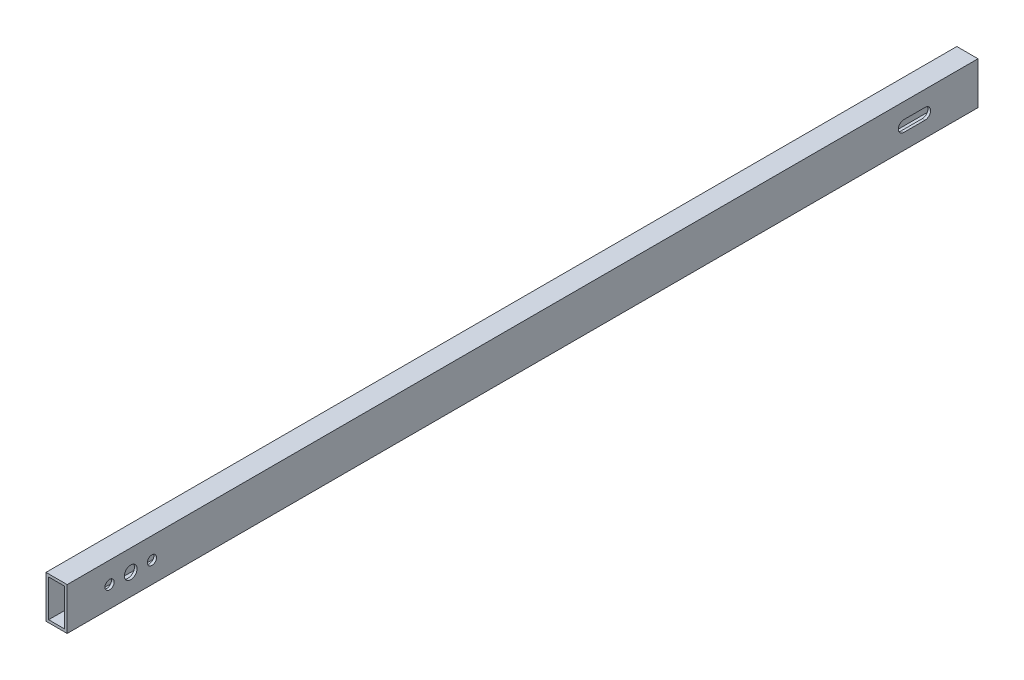
SolidWorks part; units mm, degrees
ref_plane "Front Plane" through (0, 0, 0) normal (0, 0, 1) x (1, 0, 0)
ref_plane "Top Plane" through (0, 0, 0) normal (0, 1, 0) x (1, 0, 0)
ref_plane "Right Plane" through (0, 0, 0) normal (1, 0, 0) x (0, 0, -1)
sketch "Sketch1" plane through (0, 0, 0) normal (0, 0, 1) x (1, 0, 0)
  line L1 (-6.35, -12.7) -> (6.35, -12.7)
  line L2 (-6.35, -12.7) -> (-6.35, 12.7)
  line L3 (-6.35, 12.7) -> (6.35, 12.7)
  line L4 (6.35, -12.7) -> (6.35, 12.7)
  line L6 (-6.35, 12.7) -> (6.35, -12.7) construction
  line L7 (-4.7625, -11.1125) -> (4.7625, -11.1125)
  line L8 (-4.7625, -11.1125) -> (-4.7625, 11.1125)
  line L9 (-4.7625, 11.1125) -> (4.7625, 11.1125)
  line L10 (4.7625, -11.1125) -> (4.7625, 11.1125)
  line L11 (-4.7625, -11.1125) -> (4.7625, 11.1125) construction
  line L12 (-4.7625, 11.1125) -> (4.7625, -11.1125) construction
  point P0 (0, 0)
  point P6 (0, 0)
  dimension "D1" = 25.4
  dimension "D2" = 1.5875
  dimension "D3" = 12.7
  dimension "D4" = 1.5875
  dimension "D5" = 1.5875
extrude "Boss-Extrude1" add sketch "Sketch1" along normal blind 546.1
sketch "Sketch2" plane through (6.35, 0, 0) normal (1, 0, 0) x (0, 0, -1)
  line L0 (-546.1, 0) -> (0, 0) construction
  line L1 (-546.1, -12.7) -> (-546.1, 12.7) construction
  line L2 (-508, 12.7) -> (-508, -12.7) construction
  line L3 (-31.75, 0) -> (-44.45, 0) construction
  line L4 (-31.75, -3.302) -> (-44.45, -3.302)
  line L5 (-31.75, 3.302) -> (-44.45, 3.302)
  line L6 (-546.1, 12.7) -> (0, 12.7) construction
  line L7 (-546.1, -12.7) -> (0, -12.7) construction
  line L8 (-38.1, 12.7) -> (-38.1, -12.7) construction
  circle A0 centre (-508, 0) radius 3.81
  arc A2 (-31.75, -3.302) -> (-31.75, 3.302) centre (-31.75, 0) ccw
  arc A3 (-44.45, 3.302) -> (-44.45, -3.302) centre (-44.45, 0) ccw
  circle A4 centre (-520.7, 0) radius 2.75
  circle A5 centre (-495.3, 0) radius 2.75
  point P9 (-38.1, 0)
  dimension "D1" = 7.62
  dimension "D2" = 3.302
  dimension "D6" = 5.5
  dimension "D3" = 38.1
  dimension "D4" = 12.7
  dimension "D5" = 469.9
  dimension "D7" = 25.4
extrude "Cut-Extrude1" cut sketch "Sketch2" against normal through all
sketch "Sketch3" plane through (0, 0, 546.1) normal (0, 0, 1) x (1, 0, 0)
  line L0 (-6.35, 12.7) -> (-6.35, -12.7) construction
  line L1 (-4.7625, 11.1125) -> (-6.35, 11.1125)
  line L2 (-4.7625, 11.1125) -> (-4.7625, -11.1125)
  line L3 (-4.7625, -11.1125) -> (-6.35, -11.1125)
  line L4 (-6.35, 11.1125) -> (-6.35, -11.1125)
  line L5 (-4.7625, -11.1125) -> (4.7625, -11.1125) construction
sketch "Sketch4" plane through (-6.35, 0, 0) normal (-1, 0, 0) x (0, 0, 1)
  line L0 (35.56, 0) -> (66.04, 0) construction
  line L1 (35.56, 5) -> (66.04, 5)
  line L2 (35.56, -5) -> (66.04, -5)
  line L3 (495.3, 0) -> (520.7, 0) construction
  line L4 (495.3, 5) -> (520.7, 5)
  line L5 (495.3, -5) -> (520.7, -5)
  arc A0 (35.56, 5) -> (35.56, -5) centre (35.56, 0) ccw
  arc A1 (66.04, -5) -> (66.04, 5) centre (66.04, 0) ccw
  arc A2 (495.3, 5) -> (495.3, -5) centre (495.3, 0) ccw
  arc A3 (520.7, -5) -> (520.7, 5) centre (520.7, 0) ccw
  point P2 (50.8, 0)
  point P13 (508, 0)
  dimension "D1" = 5
extrude "Cut-Extrude3" cut sketch "Sketch4" against normal up to next
sketch "Sketch5" plane through (0, -12.7, 0) normal (0, -1, 0) x (1, 0, 0)
  line L0 (-6.35, 546.1) -> (6.35, 546.1) construction
  line L1 (0, 546.1) -> (0, 0) construction
  line L2 (-6.35, 273.05) -> (6.35, 273.05) construction
  line L3 (-6.35, 546.1) -> (-6.35, 0) construction
  line L4 (6.35, 546.1) -> (6.35, 0) construction
  circle A0 centre (0, 533.4) radius 2.75
  circle A1 centre (0, 12.7) radius 2.75
  dimension "D1" = 5.5
  dimension "D2" = 12.7
extrude "Cut-Extrude5" cut sketch "Sketch5" against normal up to next
